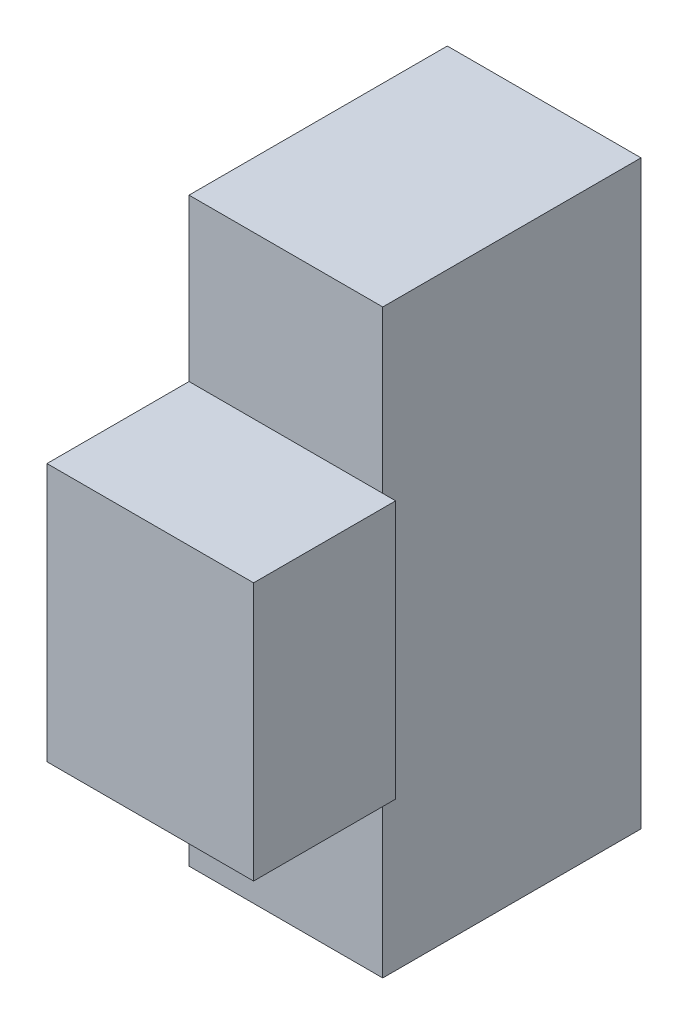
SolidWorks part; units mm, degrees
ref_plane "前视基准面" through (0, 0, 0) normal (0, 0, 1) x (1, 0, 0)
ref_plane "上视基准面" through (0, 0, 0) normal (0, 1, 0) x (1, 0, 0)
ref_plane "右视基准面" through (0, 0, 0) normal (1, 0, 0) x (0, 0, -1)
sketch "草图1" plane through (0, 0, 0) normal (1, 0, 0) x (0, 0, -1)
  line L12 (-20, 22.5) -> (-20, -22.5)
  line L13 (-20, -22.5) -> (0, -22.5)
  line L14 (0, -22.5) -> (0, 22.5)
  line L15 (0, 22.5) -> (-20, 22.5)
extrude "凸台-拉伸1" add sketch "草图1" along normal blind 15
sketch "草图2" plane through (0, 0, 0) normal (1, 0, 0) x (0, 0, -1)
  line L4 (-17.9, 13.1) -> (-17.9, -13.1)
  line L5 (-2.1, -13.1) -> (-2.1, 13.1)
  line L6 (-17.9, 13.1) -> (-17.9, -13.1)
  line L7 (-2.1, -13.1) -> (-2.1, 13.1)
  arc A4 (-2.1, 13.1) -> (-17.9, 13.1) centre (-10, 13.1) ccw
  arc A5 (-17.9, -13.1) -> (-2.1, -13.1) centre (-10, -13.1) ccw
  arc A6 (-2.1, 13.1) -> (-17.9, 13.1) centre (-10, 13.1) ccw
  arc A7 (-17.9, -13.1) -> (-2.1, -13.1) centre (-10, -13.1) ccw
  dimension "D1" = 0
sketch "草图4" plane through (0, 0, 0) normal (1, 0, 0) x (0, 0, -1)
  line L0 (-20, -10) -> (-20, 10)
  line L2 (-20, 10) -> (-31, 10)
  line L3 (-31, 10) -> (-31, -10)
  line L4 (-31, -10) -> (-20, -10)
  line L5 (-20, 22.5) -> (-20, -22.5) construction
  point P0 (-20, 0)
  point P3 (-20, 0)
  dimension "D1" = 20
  dimension "D2" = 11
extrude "凸台-拉伸2" add sketch "草图4" along normal blind 16
extrude "切除-拉伸1" cut sketch "草图2" along normal blind 11.4
